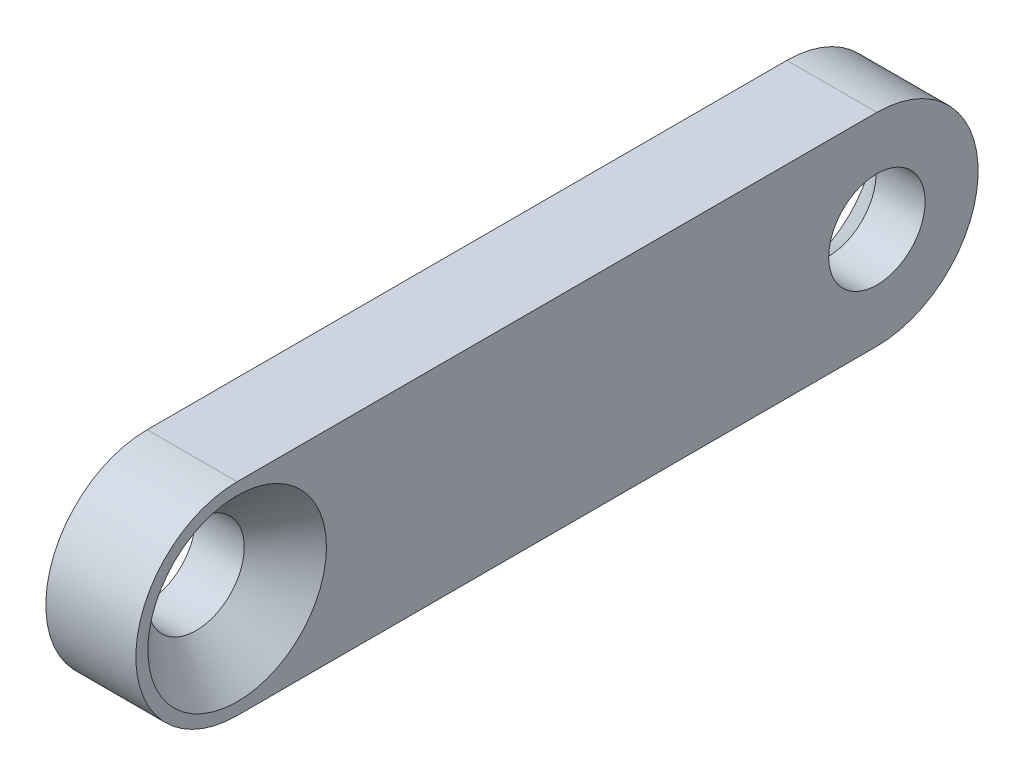
SolidWorks part; units mm, degrees
ref_plane "Front Plane" through (0, 0, 0) normal (0, 0, 1) x (1, 0, 0)
ref_plane "Top Plane" through (0, 0, 0) normal (0, 1, 0) x (1, 0, 0)
ref_plane "Right Plane" through (0, 0, 0) normal (1, 0, 0) x (0, 0, -1)
sketch "Sketch1" plane through (0, 0, 0) normal (1, 0, 0) x (0, 0, -1)
  line L0 (-11.2817, 0) -> (11.2817, 0) construction
  line L1 (-11.2817, 3.5719) -> (11.2817, 3.5719)
  line L2 (-11.2817, -3.5719) -> (11.2817, -3.5719)
  arc A0 (-11.2817, 3.5719) -> (-11.2817, -3.5719) centre (-11.2817, 0) ccw
  arc A1 (11.2817, -3.5719) -> (11.2817, 3.5719) centre (11.2817, 0) ccw
  point P2 (0, 0)
  dimension "D2" = 29.7072
  dimension "D1" = 7.1438
extrude "Boss-Extrude1" add sketch "Sketch1" along normal blind 3.175
sketch "Sketch2" plane through (0, 0, 0) normal (-1, 0, 0) x (0, 0, 1)
  point P0 (-11.2817, 0)
hole_wizard "CSK for M3 Flat Head Machine Screw1" positions "Sketch3" profile "Sketch5" countersink size "M3" standard "ANSI Metric"
sketch "Sketch3" plane through (0, 0, 0) normal (-1, 0, 0) x (0, 0, 1)
  point P0 (-11.2817, 0)
sketch "Sketch5" plane through (0, 0, -11.2817) normal (0, 1, 0) x (0, 0, 1)
  line L0 (0, 0) -> (0, 8.6415)
  line L1 (0, 8.6415) -> (1.7, 7.62)
  line L2 (1.7, 7.62) -> (1.7, 1.45)
  line L3 (1.7, 1.45) -> (3.15, 0)
  line L5 (3.15, 0) -> (0, 0)
  line L6 (-1.7, 1.45) -> (-3.15, 0) construction
  line L10 (0, 8.6415) -> (-1.7, 7.62) construction
  line L11 (0, -6.35) -> (0, 107.95) construction
  dimension "Hole Dia." = 3.4
  dimension "Hole Depth" = 7.62
  dimension "Near C'Sink Dia." = 6.3
  dimension "Near C'Sink Angle" = 90
  dimension "Drill Angle" = 118
sketch "Sketch6" plane through (3.175, 0, 0) normal (1, 0, 0) x (0, 0, -1)
  point P0 (-11.2817, 0)
hole_wizard "CSK for M3 Flat Head Machine Screw2" positions "Sketch7" profile "Sketch8" countersink size "M3" standard "ANSI Metric"
sketch "Sketch7" plane through (3.175, 0, 0) normal (1, 0, 0) x (0, 0, -1)
  point P0 (-11.2817, 0)
sketch "Sketch8" plane through (3.175, 0, 11.2817) normal (0, 1, 0) x (0, 0, -1)
  line L0 (0, 0) -> (0, 8.6415)
  line L1 (0, 8.6415) -> (1.7, 7.62)
  line L2 (1.7, 7.62) -> (1.7, 1.45)
  line L3 (1.7, 1.45) -> (3.15, 0)
  line L5 (3.15, 0) -> (0, 0)
  line L6 (-1.7, 1.45) -> (-3.15, 0) construction
  line L10 (0, 8.6415) -> (-1.7, 7.62) construction
  line L11 (0, -6.35) -> (0, 107.95) construction
  dimension "Hole Dia." = 3.4
  dimension "Hole Depth" = 7.62
  dimension "Near C'Sink Dia." = 6.3
  dimension "Near C'Sink Angle" = 90
  dimension "Drill Angle" = 118
